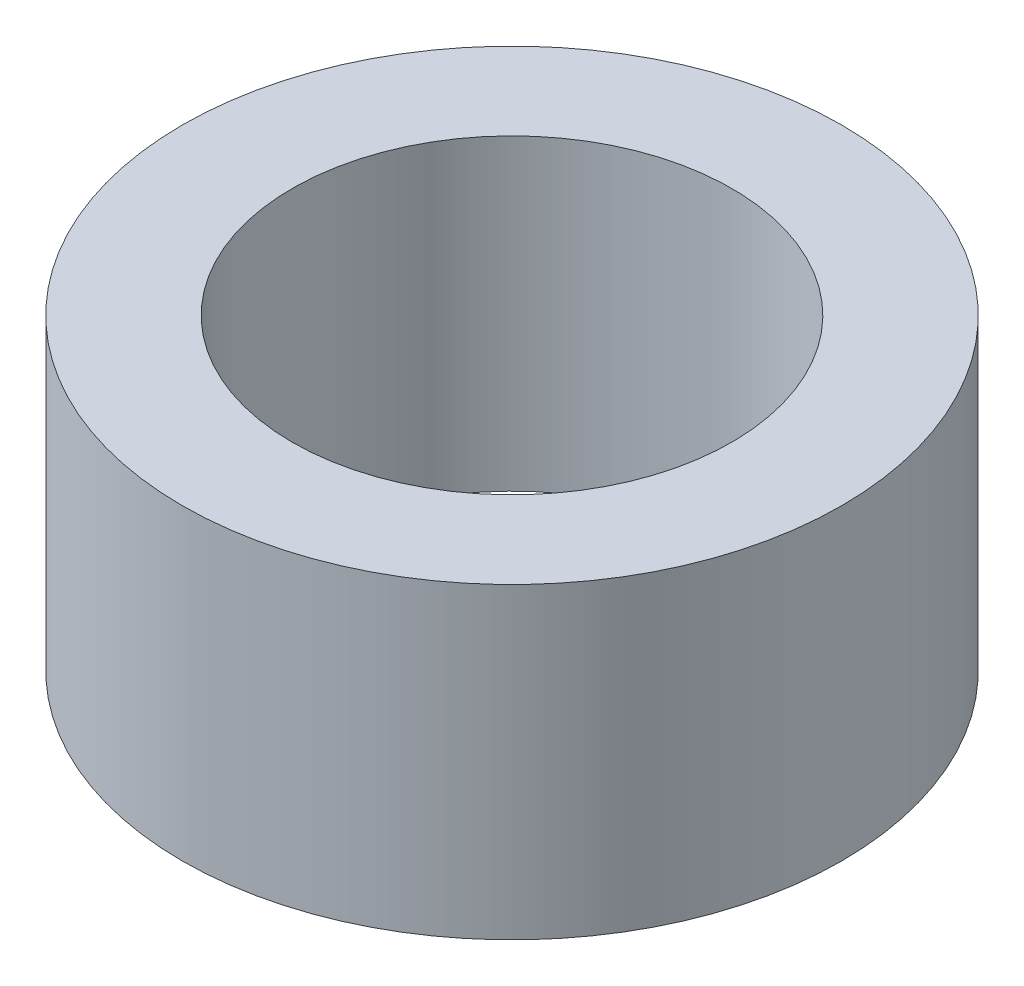
SolidWorks part; units mm, degrees
ref_plane "Front Plane" through (0, 0, 0) normal (0, 0, 1) x (1, 0, 0)
ref_plane "Top Plane" through (0, 0, 0) normal (0, 1, 0) x (1, 0, 0)
ref_plane "Right Plane" through (0, 0, 0) normal (1, 0, 0) x (0, 0, -1)
sketch "Sketch1" plane through (0, 0, 0) normal (0, 1, 0) x (1, 0, 0)
  circle A0 centre (0, 0) radius 20
  circle A1 centre (0, 0) radius 30
  dimension "D1" = 60
  dimension "D2" = 40
extrude "Boss-Extrude1" add sketch "Sketch1" along normal blind 28
